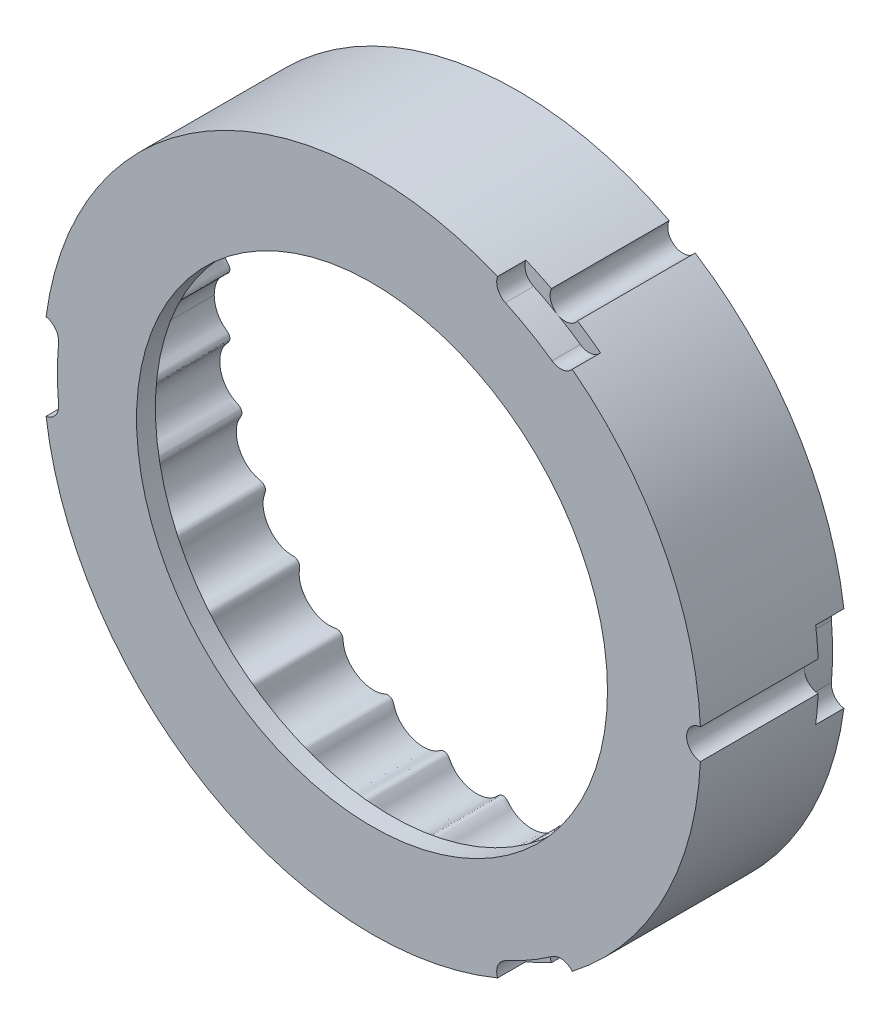
SolidWorks part; units mm, degrees
ref_plane "Plan de face" through (0, 0, 0) normal (0, 0, 1) x (1, 0, 0)
ref_plane "Plan de dessus" through (0, 0, 0) normal (0, 1, 0) x (1, 0, 0)
ref_plane "Plan de droite" through (0, 0, 0) normal (1, 0, 0) x (0, 0, -1)
sketch "Esquisse1" plane through (0, 0, 0) normal (0, 0, 1) x (1, 0, 0)
  line L0 (-1000, 0) -> (49000, 0) construction
  circle A1 centre (0, 0) radius 34.9
  spline S0 degree 4 poles (30.9263, 8.5917) (30.9244, 8.4726) (30.9128, 8.294) (30.8795, 8.0576) (30.8075, 7.7682) (30.7313, 7.5422) (30.6363, 7.3233) (30.5223, 7.1138) (30.4005, 6.9287) (30.2778, 6.7655) (30.1754, 6.608) (30.1146, 6.4469) (30.0971, 6.2542) (30.1421, 6.0755) (30.2337, 5.9301) (30.3636, 5.8076) (30.4814, 5.7308) (30.5967, 5.6632) (30.7272, 5.5824) (30.8546, 5.4968) (31.0375, 5.3568) (31.2617, 5.1464) (31.5493, 4.8022) (31.8437, 4.2901) (32.0606, 3.6436) (32.1377, 2.876) (32.0537, 2.1997) (31.8673, 1.6401) (31.6545, 1.2467) (31.4775, 0.9968) (31.3101, 0.8048) (31.1655, 0.661) (31.0397, 0.5491) (30.944, 0.4561) (30.882, 0.3799) (30.8461, 0.3281) (30.8149, 0.2732) (30.7893, 0.2154) (30.772, 0.1642) (30.7612, 0.1176) (30.7537, 0.0676) (30.7495, 0.0174) (30.7494, -0.0196) (30.7554, -0.0873) (30.767, -0.1466) (30.7842, -0.2016) (30.8067, -0.2559) (30.8409, -0.3211) (30.8874, -0.3891) (30.9471, -0.4581) (31.0185, -0.528) (31.0876, -0.5916) (31.174, -0.6713) (31.275, -0.7696) (31.4187, -0.925) (31.5905, -1.1493) (31.7652, -1.4406) (31.9227, -1.8045) (32.035, -2.1949) (32.0985, -2.6058) (32.1109, -3.0185) (32.074, -3.4266) (31.9897, -3.8245) (31.8596, -4.2068) (31.6858, -4.5663) (31.471, -4.8977) (31.2491, -5.1584) (31.0376, -5.3559) (30.847, -5.5028) (30.6865, -5.6097) (30.5113, -5.713) (30.3279, -5.8265) (30.1731, -5.9986) (30.0932, -6.2291) (30.1102, -6.46) (30.2005, -6.6565) (30.3192, -6.8188) (30.4296, -6.9724) (30.5569, -7.1717) (30.687, -7.4243) (30.8105, -7.7521) (30.9023, -8.158) (30.9393, -8.591) (30.9154, -9.0432) (30.8331, -9.4792) (30.6986, -9.8922) (30.5175, -10.2769) (30.2954, -10.6287) (30.0366, -10.942) (29.747, -11.2129) (29.4704, -11.4101) (29.2233, -11.5472) (29.008, -11.6414) (28.8315, -11.7068) (28.6421, -11.7692) (28.45, -11.8631) (28.2883, -12.027) (28.2103, -12.2249) (28.2035, -12.4054) (28.2368, -12.5701) (28.2938, -12.7158) (28.368, -12.8732) (28.4417, -13.0514) (28.5193, -13.2794) (28.5859, -13.5612) (28.6259, -13.9014) (28.6202, -14.2968) (28.5642, -14.6927) (28.4589, -15.0831) (28.3079, -15.4581) (28.1138, -15.8126) (27.8795, -16.1417) (27.6077, -16.4405) (27.3049, -16.7011) (26.9756, -16.9193) (26.6681, -17.0697) (26.3953, -17.1663) (26.1618, -17.2248) (25.972, -17.2589) (25.7701, -17.2839) (25.5569, -17.3186) (25.349, -17.4213) (25.1897, -17.6061) (25.1202, -17.827) (25.1307, -18.0426) (25.1768, -18.2381) (25.2169, -18.423) (25.254, -18.6564) (25.2723, -18.9399) (25.2546, -19.2896) (25.1768, -19.6983) (25.0382, -20.11) (24.8361, -20.5151) (24.5838, -20.8868) (24.2876, -21.2199) (23.9535, -21.5097) (23.5874, -21.7517) (23.2101, -21.9337) (22.8739, -22.0436) (22.5914, -22.1021) (22.3252, -22.1336) (22.1016, -22.1407) (21.8785, -22.1275) (21.6437, -22.1096) (21.4389, -22.1288) (21.235, -22.2214) (21.0721, -22.3967) (20.993, -22.6129) (20.9856, -22.8294) (20.9927, -23.0328) (20.9891, -23.2256) (20.9691, -23.4656) (20.9175, -23.7504) (20.8184, -24.0782) (20.6555, -24.4384) (20.4463, -24.779) (20.1313, -25.174) (19.6816, -25.5833) (19.1591, -25.8987) (18.5904, -26.1016) (18.1017, -26.1879) (17.7596, -26.203) (17.4709, -26.1826) (17.2335, -26.1428) (17.0458, -26.0984) (16.8505, -26.0411) (16.6399, -25.9918) (16.4106, -26.0101) (16.1979, -26.12) (16.0541, -26.2917) (15.9812, -26.4843) (15.9468, -26.6722) (15.9136, -26.8477) (15.8717, -27.0214) (15.8184, -27.1921) (15.7382, -27.4006) (15.5637, -27.7585) (15.2945, -28.1386) (14.9171, -28.5115) (14.4633, -28.8259) (14.0673, -29.0303) (13.6447, -29.1826) (13.2023, -29.278) (12.7692, -29.3104) (12.354, -29.2847) (12.0109, -29.2154) (11.7407, -29.1278) (11.5237, -29.0341) (11.3545, -28.9495) (11.1772, -28.8554) (10.9723, -28.7881) (10.7409, -28.7959) (10.5202, -28.8997) (10.3654, -29.0728) (10.2765, -29.2698) (10.2021, -29.4592) (10.1221, -29.6346) (10.0078, -29.8465) (9.8467, -30.087) (9.625, -30.3479) (9.2571, -30.6809) (8.748, -31.0055) (8.1785, -31.2248) (7.5795, -31.329) (7.0742, -31.3356) (6.6768, -31.2918) (6.2924, -31.1996) (5.9727, -31.0767) (5.7161, -30.9427) (5.5144, -30.8112) (5.3599, -30.6957) (5.2035, -30.5655) (5.0269, -30.4397) (4.8069, -30.3718) (4.5688, -30.3956) (4.3717, -30.5019) (4.2324, -30.653) (4.1276, -30.8125) (4.0272, -30.9603) (3.9195, -31.1029) (3.8025, -31.238) (3.6457, -31.3971) (3.3428, -31.6554) (2.8502, -31.9535) (2.2369, -32.1596) (1.5733, -32.2322) (1.0155, -32.1965) (0.5716, -32.1077) (0.1613, -31.9647) (-0.2092, -31.7754) (-0.4962, -31.5747) (-0.7089, -31.3863) (-0.8705, -31.2138) (-0.9919, -31.0688) (-1.1186, -30.9128) (-1.2838, -30.7736) (-1.5018, -30.6954) (-1.7453, -30.7105) (-1.9528, -30.8138) (-2.1099, -30.9617) (-2.2535, -31.1059) (-2.3968, -31.2349) (-2.5863, -31.3834) (-2.8299, -31.5395) (-3.1373, -31.6901) (-3.5116, -31.8163) (-3.9031, -31.8956) (-4.3058, -31.9269) (-4.7094, -31.9102) (-5.1084, -31.8461) (-5.4973, -31.7354) (-5.8703, -31.5791) (-6.2174, -31.3804) (-6.5332, -31.1424) (-6.7773, -30.902) (-6.9589, -30.6765) (-7.0914, -30.4753) (-7.1869, -30.3078) (-7.2659, -30.1527) (-7.3469, -30.0188) (-7.4577, -29.8924) (-7.6055, -29.7886) (-7.8103, -29.7311) (-8.0386, -29.7607) (-8.2296, -29.8563) (-8.3948, -29.9679) (-8.5547, -30.0672) (-8.7612, -30.1794) (-9.0211, -30.2905) (-9.3464, -30.3878) (-9.7381, -30.4504) (-10.1442, -30.4625) (-10.5582, -30.4222) (-10.9731, -30.3294) (-11.3818, -30.1823) (-11.7767, -29.98) (-12.1486, -29.7215) (-12.4679, -29.4266) (-12.7322, -29.1051) (-12.9152, -28.8064) (-13.0349, -28.5486) (-13.1142, -28.3258) (-13.1678, -28.1444) (-13.224, -27.9513) (-13.3256, -27.7603) (-13.4992, -27.6071) (-13.731, -27.5313) (-13.9616, -27.5503) (-14.1632, -27.6266) (-14.3522, -27.7017) (-14.535, -27.7628) (-14.7681, -27.8232) (-15.0538, -27.869) (-15.3957, -27.8843) (-15.7892, -27.8507) (-16.2785, -27.7463) (-16.7528, -27.5609) (-17.1946, -27.3015) (-17.5907, -26.9743) (-17.8764, -26.672) (-18.1159, -26.3439) (-18.3067, -25.9962) (-18.4295, -25.6796) (-18.5013, -25.4063) (-18.5394, -25.1743) (-18.559, -24.9871) (-18.5718, -24.7882) (-18.6117, -24.5785) (-18.7262, -24.3789) (-18.8959, -24.2506) (-19.068, -24.1957) (-19.2358, -24.1842) (-19.3915, -24.2014) (-19.5625, -24.2339) (-19.7534, -24.2613) (-19.9935, -24.2801) (-20.283, -24.2751) (-20.6226, -24.2297) (-21.0043, -24.1264) (-21.3741, -23.9741) (-21.7265, -23.7753) (-22.0523, -23.536) (-22.3477, -23.2602) (-22.6084, -22.9516) (-22.8306, -22.6144) (-23.008, -22.2566) (-23.138, -21.8836) (-23.2077, -21.5484) (-23.2339, -21.2603) (-23.2329, -21.0195) (-23.2189, -20.8273) (-23.1931, -20.6255) (-23.1714, -20.4109) (-23.2147, -20.1833) (-23.35, -19.9802) (-23.5441, -19.854) (-23.755, -19.8069) (-23.956, -19.8018) (-24.145, -19.7948) (-24.3804, -19.7731) (-24.6597, -19.7208) (-25.1025, -19.5837) (-25.5719, -19.3339) (-26.0033, -18.993) (-26.3759, -18.5716) (-26.6251, -18.2022) (-26.8231, -17.8067) (-26.9668, -17.3922) (-27.0498, -16.9817) (-27.0732, -16.6288) (-27.06, -16.3406) (-27.0307, -16.1192) (-26.9958, -15.9439) (-26.9493, -15.7714) (-26.894, -15.6014) (-26.8318, -15.421) (-26.7962, -15.2188) (-26.8307, -14.9976) (-26.9558, -14.7937) (-27.1431, -14.6595) (-27.3504, -14.5957) (-27.5492, -14.5518) (-27.7351, -14.5006) (-27.9627, -14.422) (-28.2261, -14.3016) (-28.5192, -14.1246) (-28.8279, -13.8775) (-29.1063, -13.5905) (-29.4109, -13.1873) (-29.6486, -12.7398) (-29.8135, -12.2607) (-29.9002, -11.7631) (-29.9203, -11.3641) (-29.8906, -10.9701) (-29.8207, -10.6349) (-29.7296, -10.3602) (-29.6324, -10.14) (-29.543, -9.9692) (-29.4389, -9.7943) (-29.3367, -9.6039) (-29.2926, -9.3762) (-29.3434, -9.1376) (-29.4773, -8.9486) (-29.655, -8.8263) (-29.838, -8.7434) (-30.0085, -8.6617) (-30.2156, -8.5478) (-30.4507, -8.3882) (-30.716, -8.1598) (-30.9909, -7.8477) (-31.231, -7.4857) (-31.427, -7.0776) (-31.5659, -6.6505) (-31.6473, -6.2122) (-31.6713, -5.7706) (-31.638, -5.3329) (-31.5503, -4.9233) (-31.4308, -4.5902) (-31.3037, -4.3313) (-31.1883, -4.14) (-31.0862, -3.9932) (-30.9747, -3.8536) (-30.8564, -3.7197) (-30.7286, -3.5777) (-30.6197, -3.4032) (-30.57, -3.1848) (-30.6111, -2.949) (-30.7353, -2.7553) (-30.9027, -2.6179) (-31.0677, -2.4988) (-31.2178, -2.3777) (-31.395, -2.2147) (-31.5882, -1.9992) (-31.757, -1.7611) (-31.8999, -1.5043) (-32.0017, -1.2787) (-32.0729, -1.0898) (-32.1322, -0.8972) (-32.1797, -0.7008) (-32.2109, -0.5276) (-32.2302, -0.3771) (-32.2413, -0.2512) (-32.2473, -0.1576) (-32.2503, -0.0299) (-32.2502, 0.0388) (-32.2466, 0.1794) (-32.2393, 0.2769) (-32.2254, 0.4211) (-32.2015, 0.5861) (-32.1629, 0.7796) (-32.104, 0.996) (-32.0305, 1.2085) (-31.9423, 1.415) (-31.8234, 1.6465) (-31.6896, 1.8577) (-31.544, 2.0481) (-31.3892, 2.217) (-31.2566, 2.3437) (-31.1158, 2.461) (-30.9692, 2.571) (-30.8116, 2.6874) (-30.6684, 2.8431) (-30.5791, 3.0569) (-30.5824, 3.2743) (-30.648, 3.4491) (-30.7462, 3.5961) (-30.8554, 3.7195) (-30.9782, 3.8564) (-31.1043, 4.0167) (-31.2467, 4.228) (-31.3916, 4.4977) (-31.5524, 4.9075) (-31.6691, 5.4709) (-31.6776, 6.1306) (-31.5281, 6.8579) (-31.2314, 7.526) (-30.8027, 8.104) (-30.3929, 8.4476) (-30.0923, 8.62) (-29.937, 8.6951) knots 0 0 0 0 0 0.003562 0.005342 0.007123 0.008904 0.010685 0.012466 0.014247 0.015519 0.016792 0.018065 0.019337 0.021229 0.022175 0.02312 0.024649 0.025414 0.026178 0.027707 0.029236 0.032293 0.035351 0.04107 0.046788 0.052507 0.058226 0.06127 0.064314 0.065836 0.067358 0.06888 0.070402 0.070873 0.071343 0.071813 0.072284 0.072754 0.073224 0.073459 0.073695 0.074165 0.074604 0.075042 0.075481 0.07592 0.076358 0.076797 0.077674 0.078377 0.079079 0.079782 0.080484 0.081889 0.083294 0.086104 0.088914 0.092014 0.095114 0.098215 0.101315 0.104325 0.107336 0.110347 0.113357 0.116235 0.119112 0.12055 0.121989 0.123428 0.124866 0.12664 0.128414 0.130187 0.13196 0.133373 0.134786 0.1362 0.137613 0.140439 0.143265 0.146639 0.150014 0.153388 0.156763 0.159865 0.162966 0.166068 0.169169 0.171979 0.174789 0.176194 0.177599 0.179004 0.180409 0.182167 0.183924 0.185706 0.186596 0.187487 0.188927 0.190366 0.191805 0.193245 0.196124 0.199002 0.202017 0.205033 0.208048 0.211063 0.214074 0.217086 0.220098 0.22311 0.225987 0.228865 0.230303 0.231742 0.233181 0.234619 0.236396 0.238172 0.239944 0.241716 0.243129 0.244541 0.245954 0.247367 0.250192 0.253017 0.256391 0.259764 0.263137 0.266511 0.269782 0.273052 0.276323 0.279594 0.282264 0.283598 0.284933 0.287603 0.288938 0.290273 0.291978 0.293684 0.295463 0.297243 0.298682 0.300121 0.30156 0.302999 0.305877 0.308756 0.311769 0.314783 0.317797 0.323824 0.32985 0.332862 0.33574 0.338618 0.340058 0.341497 0.342936 0.344375 0.346152 0.34793 0.349637 0.351344 0.352679 0.354014 0.355349 0.356684 0.358019 0.359354 0.362024 0.368567 0.371839 0.375111 0.378483 0.381856 0.385228 0.388601 0.391426 0.39425 0.395663 0.397075 0.398488 0.3999 0.401672 0.403443 0.40522 0.406997 0.408436 0.409875 0.411314 0.412753 0.415631 0.418509 0.421521 0.427546 0.433573 0.436587 0.439601 0.442616 0.445494 0.448372 0.449812 0.451251 0.45269 0.454129 0.455909 0.457689 0.459394 0.461099 0.462434 0.463768 0.465103 0.466438 0.467773 0.469108 0.471777 0.478318 0.484859 0.488232 0.491606 0.49498 0.498354 0.501179 0.504005 0.505418 0.50683 0.508243 0.509656 0.511429 0.513201 0.514977 0.516752 0.518191 0.519629 0.521068 0.522507 0.525384 0.528261 0.531273 0.534284 0.537295 0.540307 0.543322 0.546338 0.549353 0.552369 0.555248 0.558127 0.559566 0.561006 0.562445 0.563885 0.564776 0.565667 0.567449 0.569206 0.570963 0.572368 0.573772 0.575177 0.576582 0.579392 0.582202 0.585303 0.588404 0.591505 0.594606 0.597981 0.601356 0.604731 0.608106 0.610932 0.613759 0.615172 0.616585 0.617999 0.619412 0.621185 0.622958 0.624731 0.626505 0.627943 0.629382 0.63082 0.632259 0.635136 0.638013 0.641024 0.644034 0.650055 0.653155 0.656256 0.659357 0.662457 0.665267 0.668077 0.669482 0.670887 0.672292 0.673697 0.675453 0.677208 0.678992 0.679883 0.680775 0.682214 0.683654 0.685093 0.686533 0.689412 0.69229 0.695306 0.698322 0.701338 0.704354 0.707365 0.710376 0.713387 0.716398 0.719275 0.722153 0.723591 0.72503 0.726469 0.727907 0.729682 0.731457 0.73323 0.735002 0.736415 0.737828 0.739241 0.740654 0.74348 0.746306 0.753054 0.756428 0.759802 0.763072 0.766342 0.769612 0.772882 0.775551 0.776886 0.778221 0.779556 0.780891 0.782226 0.78356 0.785264 0.786968 0.788749 0.790529 0.791969 0.793408 0.794847 0.796287 0.799165 0.802044 0.805058 0.808073 0.811088 0.817114 0.820127 0.823139 0.826151 0.829028 0.831906 0.833345 0.834784 0.836223 0.837661 0.839438 0.841215 0.842986 0.844758 0.846171 0.847583 0.848996 0.850409 0.853234 0.856059 0.859432 0.862805 0.866178 0.86955 0.872822 0.876093 0.879364 0.882635 0.885305 0.88664 0.887975 0.88931 0.890645 0.89198 0.893315 0.895021 0.896727 0.898506 0.900284 0.901724 0.903163 0.904602 0.906041 0.908919 0.911797 0.913304 0.91481 0.916317 0.917824 0.91933 0.920837 0.92159 0.922344 0.923097 0.92385 0.924689 0.925528 0.926367 0.927206 0.928883 0.930561 0.932238 0.933916 0.935594 0.937271 0.94001 0.941379 0.942748 0.944117 0.945486 0.946856 0.948225 0.949976 0.951727 0.9536 0.954537 0.955474 0.956996 0.958518 0.96004 0.961563 0.964607 0.967651 0.973159 0.978666 0.984174 0.989682 0.994841 1 1 1 1 1 construction
  spline S1 degree 4 poles (30.75, 0) (30.75, -0.0125) (30.751, -0.0374) (30.7554, -0.0873) (30.767, -0.1466) (30.7842, -0.2016) (30.8067, -0.2559) (30.8409, -0.3211) (30.8874, -0.3891) (30.9471, -0.4581) (31.0185, -0.528) (31.0876, -0.5916) (31.174, -0.6713) (31.275, -0.7696) (31.4187, -0.925) (31.5905, -1.1493) (31.7652, -1.4406) (31.9227, -1.8045) (32.035, -2.1949) (32.0985, -2.6058) (32.1109, -3.0185) (32.074, -3.4266) (31.9897, -3.8245) (31.8596, -4.2068) (31.6858, -4.5663) (31.471, -4.8977) (31.2491, -5.1584) (31.0376, -5.3559) (30.847, -5.5028) (30.6865, -5.6097) (30.5113, -5.713) (30.3279, -5.8265) (30.1731, -5.9986) (30.0932, -6.2291) (30.1102, -6.46) (30.2005, -6.6565) (30.3192, -6.8188) (30.4296, -6.9724) (30.5569, -7.1717) (30.687, -7.4243) (30.8105, -7.7521) (30.9023, -8.158) (30.9393, -8.591) (30.9154, -9.0432) (30.8331, -9.4792) (30.6986, -9.8922) (30.5175, -10.2769) (30.2954, -10.6287) (30.0366, -10.942) (29.747, -11.2129) (29.4704, -11.4101) (29.2233, -11.5472) (29.008, -11.6414) (28.8315, -11.7068) (28.6421, -11.7692) (28.45, -11.8631) (28.2883, -12.027) (28.2103, -12.2249) (28.2035, -12.4054) (28.2368, -12.5701) (28.2938, -12.7158) (28.368, -12.8732) (28.4417, -13.0514) (28.5193, -13.2794) (28.5859, -13.5612) (28.6259, -13.9014) (28.6202, -14.2968) (28.5642, -14.6927) (28.4589, -15.0831) (28.3079, -15.4581) (28.1138, -15.8126) (27.8795, -16.1417) (27.6077, -16.4405) (27.3049, -16.7011) (26.9756, -16.9193) (26.6681, -17.0697) (26.3953, -17.1663) (26.1618, -17.2248) (25.972, -17.2589) (25.7701, -17.2839) (25.5569, -17.3186) (25.349, -17.4213) (25.1897, -17.6061) (25.1202, -17.827) (25.1307, -18.0426) (25.1768, -18.2381) (25.2169, -18.423) (25.254, -18.6564) (25.2723, -18.9399) (25.2546, -19.2896) (25.1768, -19.6983) (25.0382, -20.11) (24.8361, -20.5151) (24.5838, -20.8868) (24.2876, -21.2199) (23.9535, -21.5097) (23.5874, -21.7517) (23.2101, -21.9337) (22.8739, -22.0436) (22.5914, -22.1021) (22.3252, -22.1336) (22.1016, -22.1407) (21.8785, -22.1275) (21.6437, -22.1096) (21.4389, -22.1288) (21.235, -22.2214) (21.0721, -22.3967) (20.993, -22.6129) (20.9856, -22.8294) (20.9927, -23.0328) (20.9891, -23.2256) (20.9691, -23.4656) (20.9175, -23.7504) (20.8184, -24.0782) (20.6555, -24.4384) (20.4463, -24.779) (20.1313, -25.174) (19.6816, -25.5833) (19.1591, -25.8987) (18.5904, -26.1016) (18.1017, -26.1879) (17.7596, -26.203) (17.4709, -26.1826) (17.2335, -26.1428) (17.0458, -26.0984) (16.8505, -26.0411) (16.6399, -25.9918) (16.4106, -26.0101) (16.1979, -26.12) (16.0541, -26.2917) (15.9812, -26.4843) (15.9468, -26.6722) (15.9136, -26.8477) (15.8717, -27.0214) (15.8184, -27.1921) (15.7382, -27.4006) (15.5637, -27.7585) (15.2945, -28.1386) (14.9171, -28.5115) (14.4633, -28.8259) (14.0673, -29.0303) (13.6447, -29.1826) (13.2023, -29.278) (12.7692, -29.3104) (12.354, -29.2847) (12.0109, -29.2154) (11.7407, -29.1278) (11.5237, -29.0341) (11.3545, -28.9495) (11.1772, -28.8554) (10.9723, -28.7881) (10.7409, -28.7959) (10.5202, -28.8997) (10.3654, -29.0728) (10.2765, -29.2698) (10.2021, -29.4592) (10.1221, -29.6346) (10.0078, -29.8465) (9.8467, -30.087) (9.625, -30.3479) (9.2571, -30.6809) (8.748, -31.0055) (8.1785, -31.2248) (7.5795, -31.329) (7.0742, -31.3356) (6.6768, -31.2918) (6.2924, -31.1996) (5.9727, -31.0767) (5.7161, -30.9427) (5.5144, -30.8112) (5.3599, -30.6957) (5.2035, -30.5655) (5.0269, -30.4397) (4.8069, -30.3718) (4.5688, -30.3956) (4.3717, -30.5019) (4.2324, -30.653) (4.1276, -30.8125) (4.0272, -30.9603) (3.9195, -31.1029) (3.8025, -31.238) (3.6457, -31.3971) (3.3428, -31.6554) (2.8502, -31.9535) (2.2369, -32.1596) (1.5733, -32.2322) (1.0155, -32.1965) (0.5716, -32.1077) (0.1613, -31.9647) (-0.2092, -31.7754) (-0.4962, -31.5747) (-0.7089, -31.3863) (-0.8705, -31.2138) (-0.9919, -31.0688) (-1.1186, -30.9128) (-1.2838, -30.7736) (-1.5018, -30.6954) (-1.7453, -30.7105) (-1.9528, -30.8138) (-2.1099, -30.9617) (-2.2535, -31.1059) (-2.3968, -31.2349) (-2.5863, -31.3834) (-2.8299, -31.5395) (-3.1373, -31.6901) (-3.5116, -31.8163) (-3.9031, -31.8956) (-4.3058, -31.9269) (-4.7094, -31.9102) (-5.1084, -31.8461) (-5.4973, -31.7354) (-5.8703, -31.5791) (-6.2174, -31.3804) (-6.5332, -31.1424) (-6.7773, -30.902) (-6.9589, -30.6765) (-7.0914, -30.4753) (-7.1869, -30.3078) (-7.2659, -30.1527) (-7.3469, -30.0188) (-7.4577, -29.8924) (-7.6055, -29.7886) (-7.8103, -29.7311) (-8.0386, -29.7607) (-8.2296, -29.8563) (-8.3948, -29.9679) (-8.5547, -30.0672) (-8.7612, -30.1794) (-9.0211, -30.2905) (-9.3464, -30.3878) (-9.7381, -30.4504) (-10.1442, -30.4625) (-10.5582, -30.4222) (-10.9731, -30.3294) (-11.3818, -30.1823) (-11.7767, -29.98) (-12.1486, -29.7215) (-12.4679, -29.4266) (-12.7322, -29.1051) (-12.9152, -28.8064) (-13.0349, -28.5486) (-13.1142, -28.3258) (-13.1678, -28.1444) (-13.224, -27.9513) (-13.3256, -27.7603) (-13.4992, -27.6071) (-13.731, -27.5313) (-13.9616, -27.5503) (-14.1632, -27.6266) (-14.3522, -27.7017) (-14.535, -27.7628) (-14.7681, -27.8232) (-15.0538, -27.869) (-15.3957, -27.8843) (-15.7892, -27.8507) (-16.2785, -27.7463) (-16.7528, -27.5609) (-17.1946, -27.3015) (-17.5907, -26.9743) (-17.8764, -26.672) (-18.1159, -26.3439) (-18.3067, -25.9962) (-18.4295, -25.6796) (-18.5013, -25.4063) (-18.5394, -25.1743) (-18.559, -24.9871) (-18.5718, -24.7882) (-18.6117, -24.5785) (-18.7262, -24.3789) (-18.8959, -24.2506) (-19.068, -24.1957) (-19.2358, -24.1842) (-19.3915, -24.2014) (-19.5625, -24.2339) (-19.7534, -24.2613) (-19.9935, -24.2801) (-20.283, -24.2751) (-20.6226, -24.2297) (-21.0043, -24.1264) (-21.3741, -23.9741) (-21.7265, -23.7753) (-22.0523, -23.536) (-22.3477, -23.2602) (-22.6084, -22.9516) (-22.8306, -22.6144) (-23.008, -22.2566) (-23.138, -21.8836) (-23.2077, -21.5484) (-23.2339, -21.2603) (-23.2329, -21.0195) (-23.2189, -20.8273) (-23.1931, -20.6255) (-23.1714, -20.4109) (-23.2147, -20.1833) (-23.35, -19.9802) (-23.5441, -19.854) (-23.755, -19.8069) (-23.956, -19.8018) (-24.145, -19.7948) (-24.3804, -19.7731) (-24.6597, -19.7208) (-25.1025, -19.5837) (-25.5719, -19.3339) (-26.0033, -18.993) (-26.3759, -18.5716) (-26.6251, -18.2022) (-26.8231, -17.8067) (-26.9668, -17.3922) (-27.0498, -16.9817) (-27.0732, -16.6288) (-27.06, -16.3406) (-27.0307, -16.1192) (-26.9958, -15.9439) (-26.9493, -15.7714) (-26.894, -15.6014) (-26.8318, -15.421) (-26.7962, -15.2188) (-26.8307, -14.9976) (-26.9558, -14.7937) (-27.1431, -14.6595) (-27.3504, -14.5957) (-27.5492, -14.5518) (-27.7351, -14.5006) (-27.9627, -14.422) (-28.2261, -14.3016) (-28.5192, -14.1246) (-28.8279, -13.8775) (-29.1063, -13.5905) (-29.4109, -13.1873) (-29.6486, -12.7398) (-29.8135, -12.2607) (-29.9002, -11.7631) (-29.9203, -11.3641) (-29.8906, -10.9701) (-29.8207, -10.6349) (-29.7296, -10.3602) (-29.6324, -10.14) (-29.543, -9.9692) (-29.4389, -9.7943) (-29.3367, -9.6039) (-29.2926, -9.3762) (-29.3434, -9.1376) (-29.4773, -8.9486) (-29.655, -8.8263) (-29.838, -8.7434) (-30.0085, -8.6617) (-30.2156, -8.5478) (-30.4507, -8.3882) (-30.716, -8.1598) (-30.9909, -7.8477) (-31.231, -7.4857) (-31.427, -7.0776) (-31.5659, -6.6505) (-31.6473, -6.2122) (-31.6713, -5.7706) (-31.638, -5.3329) (-31.5503, -4.9233) (-31.4308, -4.5902) (-31.3037, -4.3313) (-31.1883, -4.14) (-31.0862, -3.9932) (-30.9747, -3.8536) (-30.8564, -3.7197) (-30.7286, -3.5777) (-30.6197, -3.4032) (-30.57, -3.1848) (-30.6111, -2.949) (-30.7353, -2.7553) (-30.9027, -2.6179) (-31.0677, -2.4988) (-31.2178, -2.3777) (-31.395, -2.2147) (-31.5882, -1.9992) (-31.757, -1.7611) (-31.8999, -1.5043) (-32.0017, -1.2787) (-32.0729, -1.0898) (-32.1322, -0.8972) (-32.1797, -0.7008) (-32.2109, -0.5276) (-32.2302, -0.3771) (-32.2413, -0.2512) (-32.2473, -0.1576) (-32.2495, -0.0645) (-32.25, -0.0214) (-32.25, 0) knots 0.074165 0.074165 0.074165 0.074165 0.074165 0.074604 0.075042 0.075481 0.07592 0.076358 0.076797 0.077674 0.078377 0.079079 0.079782 0.080484 0.081889 0.083294 0.086104 0.088914 0.092014 0.095114 0.098215 0.101315 0.104325 0.107336 0.110347 0.113357 0.116235 0.119112 0.12055 0.121989 0.123428 0.124866 0.12664 0.128414 0.130187 0.13196 0.133373 0.134786 0.1362 0.137613 0.140439 0.143265 0.146639 0.150014 0.153388 0.156763 0.159865 0.162966 0.166068 0.169169 0.171979 0.174789 0.176194 0.177599 0.179004 0.180409 0.182167 0.183924 0.185706 0.186596 0.187487 0.188927 0.190366 0.191805 0.193245 0.196124 0.199002 0.202017 0.205033 0.208048 0.211063 0.214074 0.217086 0.220098 0.22311 0.225987 0.228865 0.230303 0.231742 0.233181 0.234619 0.236396 0.238172 0.239944 0.241716 0.243129 0.244541 0.245954 0.247367 0.250192 0.253017 0.256391 0.259764 0.263137 0.266511 0.269782 0.273052 0.276323 0.279594 0.282264 0.283598 0.284933 0.287603 0.288938 0.290273 0.291978 0.293684 0.295463 0.297243 0.298682 0.300121 0.30156 0.302999 0.305877 0.308756 0.311769 0.314783 0.317797 0.323824 0.32985 0.332862 0.33574 0.338618 0.340058 0.341497 0.342936 0.344375 0.346152 0.34793 0.349637 0.351344 0.352679 0.354014 0.355349 0.356684 0.358019 0.359354 0.362024 0.368567 0.371839 0.375111 0.378483 0.381856 0.385228 0.388601 0.391426 0.39425 0.395663 0.397075 0.398488 0.3999 0.401672 0.403443 0.40522 0.406997 0.408436 0.409875 0.411314 0.412753 0.415631 0.418509 0.421521 0.427546 0.433573 0.436587 0.439601 0.442616 0.445494 0.448372 0.449812 0.451251 0.45269 0.454129 0.455909 0.457689 0.459394 0.461099 0.462434 0.463768 0.465103 0.466438 0.467773 0.469108 0.471777 0.478318 0.484859 0.488232 0.491606 0.49498 0.498354 0.501179 0.504005 0.505418 0.50683 0.508243 0.509656 0.511429 0.513201 0.514977 0.516752 0.518191 0.519629 0.521068 0.522507 0.525384 0.528261 0.531273 0.534284 0.537295 0.540307 0.543322 0.546338 0.549353 0.552369 0.555248 0.558127 0.559566 0.561006 0.562445 0.563885 0.564776 0.565667 0.567449 0.569206 0.570963 0.572368 0.573772 0.575177 0.576582 0.579392 0.582202 0.585303 0.588404 0.591505 0.594606 0.597981 0.601356 0.604731 0.608106 0.610932 0.613759 0.615172 0.616585 0.617999 0.619412 0.621185 0.622958 0.624731 0.626505 0.627943 0.629382 0.63082 0.632259 0.635136 0.638013 0.641024 0.644034 0.650055 0.653155 0.656256 0.659357 0.662457 0.665267 0.668077 0.669482 0.670887 0.672292 0.673697 0.675453 0.677208 0.678992 0.679883 0.680775 0.682214 0.683654 0.685093 0.686533 0.689412 0.69229 0.695306 0.698322 0.701338 0.704354 0.707365 0.710376 0.713387 0.716398 0.719275 0.722153 0.723591 0.72503 0.726469 0.727907 0.729682 0.731457 0.73323 0.735002 0.736415 0.737828 0.739241 0.740654 0.74348 0.746306 0.753054 0.756428 0.759802 0.763072 0.766342 0.769612 0.772882 0.775551 0.776886 0.778221 0.779556 0.780891 0.782226 0.78356 0.785264 0.786968 0.788749 0.790529 0.791969 0.793408 0.794847 0.796287 0.799165 0.802044 0.805058 0.808073 0.811088 0.817114 0.820127 0.823139 0.826151 0.829028 0.831906 0.833345 0.834784 0.836223 0.837661 0.839438 0.841215 0.842986 0.844758 0.846171 0.847583 0.848996 0.850409 0.853234 0.856059 0.859432 0.862805 0.866178 0.86955 0.872822 0.876093 0.879364 0.882635 0.885305 0.88664 0.887975 0.88931 0.890645 0.89198 0.893315 0.895021 0.896727 0.898506 0.900284 0.901724 0.903163 0.904602 0.906041 0.908919 0.911797 0.913304 0.91481 0.916317 0.917824 0.91933 0.920837 0.92159 0.922344 0.923097 0.92385 0.92385 0.92385 0.92385 0.92385
  spline S2 degree 4 poles (30.75, 0) (30.75, 0.0125) (30.751, 0.0374) (30.7554, 0.0873) (30.767, 0.1466) (30.7842, 0.2016) (30.8067, 0.2559) (30.8409, 0.3211) (30.8874, 0.3891) (30.9471, 0.4581) (31.0185, 0.528) (31.0876, 0.5916) (31.174, 0.6713) (31.275, 0.7696) (31.4187, 0.925) (31.5905, 1.1493) (31.7652, 1.4406) (31.9227, 1.8045) (32.035, 2.1949) (32.0985, 2.6058) (32.1109, 3.0185) (32.074, 3.4266) (31.9897, 3.8245) (31.8596, 4.2068) (31.6858, 4.5663) (31.471, 4.8977) (31.2491, 5.1584) (31.0376, 5.3559) (30.847, 5.5028) (30.6865, 5.6097) (30.5113, 5.713) (30.3279, 5.8265) (30.1731, 5.9986) (30.0932, 6.2291) (30.1102, 6.46) (30.2005, 6.6565) (30.3192, 6.8188) (30.4296, 6.9724) (30.5569, 7.1717) (30.687, 7.4243) (30.8105, 7.7521) (30.9023, 8.158) (30.9393, 8.591) (30.9154, 9.0432) (30.8331, 9.4792) (30.6986, 9.8922) (30.5175, 10.2769) (30.2954, 10.6287) (30.0366, 10.942) (29.747, 11.2129) (29.4704, 11.4101) (29.2233, 11.5472) (29.008, 11.6414) (28.8315, 11.7068) (28.6421, 11.7692) (28.45, 11.8631) (28.2883, 12.027) (28.2103, 12.2249) (28.2035, 12.4054) (28.2368, 12.5701) (28.2938, 12.7158) (28.368, 12.8732) (28.4417, 13.0514) (28.5193, 13.2794) (28.5859, 13.5612) (28.6259, 13.9014) (28.6202, 14.2968) (28.5642, 14.6927) (28.4589, 15.0831) (28.3079, 15.4581) (28.1138, 15.8126) (27.8795, 16.1417) (27.6077, 16.4405) (27.3049, 16.7011) (26.9756, 16.9193) (26.6681, 17.0697) (26.3953, 17.1663) (26.1618, 17.2248) (25.972, 17.2589) (25.7701, 17.2839) (25.5569, 17.3186) (25.349, 17.4213) (25.1897, 17.6061) (25.1202, 17.827) (25.1307, 18.0426) (25.1768, 18.2381) (25.2169, 18.423) (25.254, 18.6564) (25.2723, 18.9399) (25.2546, 19.2896) (25.1768, 19.6983) (25.0382, 20.11) (24.8361, 20.5151) (24.5838, 20.8868) (24.2876, 21.2199) (23.9535, 21.5097) (23.5874, 21.7517) (23.2101, 21.9337) (22.8739, 22.0436) (22.5914, 22.1021) (22.3252, 22.1336) (22.1016, 22.1407) (21.8785, 22.1275) (21.6437, 22.1096) (21.4389, 22.1288) (21.235, 22.2214) (21.0721, 22.3967) (20.993, 22.6129) (20.9856, 22.8294) (20.9927, 23.0328) (20.9891, 23.2256) (20.9691, 23.4656) (20.9175, 23.7504) (20.8184, 24.0782) (20.6555, 24.4384) (20.4463, 24.779) (20.1313, 25.174) (19.6816, 25.5833) (19.1591, 25.8987) (18.5904, 26.1016) (18.1017, 26.1879) (17.7596, 26.203) (17.4709, 26.1826) (17.2335, 26.1428) (17.0458, 26.0984) (16.8505, 26.0411) (16.6399, 25.9918) (16.4106, 26.0101) (16.1979, 26.12) (16.0541, 26.2917) (15.9812, 26.4843) (15.9468, 26.6722) (15.9136, 26.8477) (15.8717, 27.0214) (15.8184, 27.1921) (15.7382, 27.4006) (15.5637, 27.7585) (15.2945, 28.1386) (14.9171, 28.5115) (14.4633, 28.8259) (14.0673, 29.0303) (13.6447, 29.1826) (13.2023, 29.278) (12.7692, 29.3104) (12.354, 29.2847) (12.0109, 29.2154) (11.7407, 29.1278) (11.5237, 29.0341) (11.3545, 28.9495) (11.1772, 28.8554) (10.9723, 28.7881) (10.7409, 28.7959) (10.5202, 28.8997) (10.3654, 29.0728) (10.2765, 29.2698) (10.2021, 29.4592) (10.1221, 29.6346) (10.0078, 29.8465) (9.8467, 30.087) (9.625, 30.3479) (9.2571, 30.6809) (8.748, 31.0055) (8.1785, 31.2248) (7.5795, 31.329) (7.0742, 31.3356) (6.6768, 31.2918) (6.2924, 31.1996) (5.9727, 31.0767) (5.7161, 30.9427) (5.5144, 30.8112) (5.3599, 30.6957) (5.2035, 30.5655) (5.0269, 30.4397) (4.8069, 30.3718) (4.5688, 30.3956) (4.3717, 30.5019) (4.2324, 30.653) (4.1276, 30.8125) (4.0272, 30.9603) (3.9195, 31.1029) (3.8025, 31.238) (3.6457, 31.3971) (3.3428, 31.6554) (2.8502, 31.9535) (2.2369, 32.1596) (1.5733, 32.2322) (1.0155, 32.1965) (0.5716, 32.1077) (0.1613, 31.9647) (-0.2092, 31.7754) (-0.4962, 31.5747) (-0.7089, 31.3863) (-0.8705, 31.2138) (-0.9919, 31.0688) (-1.1186, 30.9128) (-1.2838, 30.7736) (-1.5018, 30.6954) (-1.7453, 30.7105) (-1.9528, 30.8138) (-2.1099, 30.9617) (-2.2535, 31.1059) (-2.3968, 31.2349) (-2.5863, 31.3834) (-2.8299, 31.5395) (-3.1373, 31.6901) (-3.5116, 31.8163) (-3.9031, 31.8956) (-4.3058, 31.9269) (-4.7094, 31.9102) (-5.1084, 31.8461) (-5.4973, 31.7354) (-5.8703, 31.5791) (-6.2174, 31.3804) (-6.5332, 31.1424) (-6.7773, 30.902) (-6.9589, 30.6765) (-7.0914, 30.4753) (-7.1869, 30.3078) (-7.2659, 30.1527) (-7.3469, 30.0188) (-7.4577, 29.8924) (-7.6055, 29.7886) (-7.8103, 29.7311) (-8.0386, 29.7607) (-8.2296, 29.8563) (-8.3948, 29.9679) (-8.5547, 30.0672) (-8.7612, 30.1794) (-9.0211, 30.2905) (-9.3464, 30.3878) (-9.7381, 30.4504) (-10.1442, 30.4625) (-10.5582, 30.4222) (-10.9731, 30.3294) (-11.3818, 30.1823) (-11.7767, 29.98) (-12.1486, 29.7215) (-12.4679, 29.4266) (-12.7322, 29.1051) (-12.9152, 28.8064) (-13.0349, 28.5486) (-13.1142, 28.3258) (-13.1678, 28.1444) (-13.224, 27.9513) (-13.3256, 27.7603) (-13.4992, 27.6071) (-13.731, 27.5313) (-13.9616, 27.5503) (-14.1632, 27.6266) (-14.3522, 27.7017) (-14.535, 27.7628) (-14.7681, 27.8232) (-15.0538, 27.869) (-15.3957, 27.8843) (-15.7892, 27.8507) (-16.2785, 27.7463) (-16.7528, 27.5609) (-17.1946, 27.3015) (-17.5907, 26.9743) (-17.8764, 26.672) (-18.1159, 26.3439) (-18.3067, 25.9962) (-18.4295, 25.6796) (-18.5013, 25.4063) (-18.5394, 25.1743) (-18.559, 24.9871) (-18.5718, 24.7882) (-18.6117, 24.5785) (-18.7262, 24.3789) (-18.8959, 24.2506) (-19.068, 24.1957) (-19.2358, 24.1842) (-19.3915, 24.2014) (-19.5625, 24.2339) (-19.7534, 24.2613) (-19.9935, 24.2801) (-20.283, 24.2751) (-20.6226, 24.2297) (-21.0043, 24.1264) (-21.3741, 23.9741) (-21.7265, 23.7753) (-22.0523, 23.536) (-22.3477, 23.2602) (-22.6084, 22.9516) (-22.8306, 22.6144) (-23.008, 22.2566) (-23.138, 21.8836) (-23.2077, 21.5484) (-23.2339, 21.2603) (-23.2329, 21.0195) (-23.2189, 20.8273) (-23.1931, 20.6255) (-23.1714, 20.4109) (-23.2147, 20.1833) (-23.35, 19.9802) (-23.5441, 19.854) (-23.755, 19.8069) (-23.956, 19.8018) (-24.145, 19.7948) (-24.3804, 19.7731) (-24.6597, 19.7208) (-25.1025, 19.5837) (-25.5719, 19.3339) (-26.0033, 18.993) (-26.3759, 18.5716) (-26.6251, 18.2022) (-26.8231, 17.8067) (-26.9668, 17.3922) (-27.0498, 16.9817) (-27.0732, 16.6288) (-27.06, 16.3406) (-27.0307, 16.1192) (-26.9958, 15.9439) (-26.9493, 15.7714) (-26.894, 15.6014) (-26.8318, 15.421) (-26.7962, 15.2188) (-26.8307, 14.9976) (-26.9558, 14.7937) (-27.1431, 14.6595) (-27.3504, 14.5957) (-27.5492, 14.5518) (-27.7351, 14.5006) (-27.9627, 14.422) (-28.2261, 14.3016) (-28.5192, 14.1246) (-28.8279, 13.8775) (-29.1063, 13.5905) (-29.4109, 13.1873) (-29.6486, 12.7398) (-29.8135, 12.2607) (-29.9002, 11.7631) (-29.9203, 11.3641) (-29.8906, 10.9701) (-29.8207, 10.6349) (-29.7296, 10.3602) (-29.6324, 10.14) (-29.543, 9.9692) (-29.4389, 9.7943) (-29.3367, 9.6039) (-29.2926, 9.3762) (-29.3434, 9.1376) (-29.4773, 8.9486) (-29.655, 8.8263) (-29.838, 8.7434) (-30.0085, 8.6617) (-30.2156, 8.5478) (-30.4507, 8.3882) (-30.716, 8.1598) (-30.9909, 7.8477) (-31.231, 7.4857) (-31.427, 7.0776) (-31.5659, 6.6505) (-31.6473, 6.2122) (-31.6713, 5.7706) (-31.638, 5.3329) (-31.5503, 4.9233) (-31.4308, 4.5902) (-31.3037, 4.3313) (-31.1883, 4.14) (-31.0862, 3.9932) (-30.9747, 3.8536) (-30.8564, 3.7197) (-30.7286, 3.5777) (-30.6197, 3.4032) (-30.57, 3.1848) (-30.6111, 2.949) (-30.7353, 2.7553) (-30.9027, 2.6179) (-31.0677, 2.4988) (-31.2178, 2.3777) (-31.395, 2.2147) (-31.5882, 1.9992) (-31.757, 1.7611) (-31.8999, 1.5043) (-32.0017, 1.2787) (-32.0729, 1.0898) (-32.1322, 0.8972) (-32.1797, 0.7008) (-32.2109, 0.5276) (-32.2302, 0.3771) (-32.2413, 0.2512) (-32.2473, 0.1576) (-32.2495, 0.0645) (-32.25, 0.0214) (-32.25, 0) knots 0.074165 0.074165 0.074165 0.074165 0.074165 0.074604 0.075042 0.075481 0.07592 0.076358 0.076797 0.077674 0.078377 0.079079 0.079782 0.080484 0.081889 0.083294 0.086104 0.088914 0.092014 0.095114 0.098215 0.101315 0.104325 0.107336 0.110347 0.113357 0.116235 0.119112 0.12055 0.121989 0.123428 0.124866 0.12664 0.128414 0.130187 0.13196 0.133373 0.134786 0.1362 0.137613 0.140439 0.143265 0.146639 0.150014 0.153388 0.156763 0.159865 0.162966 0.166068 0.169169 0.171979 0.174789 0.176194 0.177599 0.179004 0.180409 0.182167 0.183924 0.185706 0.186596 0.187487 0.188927 0.190366 0.191805 0.193245 0.196124 0.199002 0.202017 0.205033 0.208048 0.211063 0.214074 0.217086 0.220098 0.22311 0.225987 0.228865 0.230303 0.231742 0.233181 0.234619 0.236396 0.238172 0.239944 0.241716 0.243129 0.244541 0.245954 0.247367 0.250192 0.253017 0.256391 0.259764 0.263137 0.266511 0.269782 0.273052 0.276323 0.279594 0.282264 0.283598 0.284933 0.287603 0.288938 0.290273 0.291978 0.293684 0.295463 0.297243 0.298682 0.300121 0.30156 0.302999 0.305877 0.308756 0.311769 0.314783 0.317797 0.323824 0.32985 0.332862 0.33574 0.338618 0.340058 0.341497 0.342936 0.344375 0.346152 0.34793 0.349637 0.351344 0.352679 0.354014 0.355349 0.356684 0.358019 0.359354 0.362024 0.368567 0.371839 0.375111 0.378483 0.381856 0.385228 0.388601 0.391426 0.39425 0.395663 0.397075 0.398488 0.3999 0.401672 0.403443 0.40522 0.406997 0.408436 0.409875 0.411314 0.412753 0.415631 0.418509 0.421521 0.427546 0.433573 0.436587 0.439601 0.442616 0.445494 0.448372 0.449812 0.451251 0.45269 0.454129 0.455909 0.457689 0.459394 0.461099 0.462434 0.463768 0.465103 0.466438 0.467773 0.469108 0.471777 0.478318 0.484859 0.488232 0.491606 0.49498 0.498354 0.501179 0.504005 0.505418 0.50683 0.508243 0.509656 0.511429 0.513201 0.514977 0.516752 0.518191 0.519629 0.521068 0.522507 0.525384 0.528261 0.531273 0.534284 0.537295 0.540307 0.543322 0.546338 0.549353 0.552369 0.555248 0.558127 0.559566 0.561006 0.562445 0.563885 0.564776 0.565667 0.567449 0.569206 0.570963 0.572368 0.573772 0.575177 0.576582 0.579392 0.582202 0.585303 0.588404 0.591505 0.594606 0.597981 0.601356 0.604731 0.608106 0.610932 0.613759 0.615172 0.616585 0.617999 0.619412 0.621185 0.622958 0.624731 0.626505 0.627943 0.629382 0.63082 0.632259 0.635136 0.638013 0.641024 0.644034 0.650055 0.653155 0.656256 0.659357 0.662457 0.665267 0.668077 0.669482 0.670887 0.672292 0.673697 0.675453 0.677208 0.678992 0.679883 0.680775 0.682214 0.683654 0.685093 0.686533 0.689412 0.69229 0.695306 0.698322 0.701338 0.704354 0.707365 0.710376 0.713387 0.716398 0.719275 0.722153 0.723591 0.72503 0.726469 0.727907 0.729682 0.731457 0.73323 0.735002 0.736415 0.737828 0.739241 0.740654 0.74348 0.746306 0.753054 0.756428 0.759802 0.763072 0.766342 0.769612 0.772882 0.775551 0.776886 0.778221 0.779556 0.780891 0.782226 0.78356 0.785264 0.786968 0.788749 0.790529 0.791969 0.793408 0.794847 0.796287 0.799165 0.802044 0.805058 0.808073 0.811088 0.817114 0.820127 0.823139 0.826151 0.829028 0.831906 0.833345 0.834784 0.836223 0.837661 0.839438 0.841215 0.842986 0.844758 0.846171 0.847583 0.848996 0.850409 0.853234 0.856059 0.859432 0.862805 0.866178 0.86955 0.872822 0.876093 0.879364 0.882635 0.885305 0.88664 0.887975 0.88931 0.890645 0.89198 0.893315 0.895021 0.896727 0.898506 0.900284 0.901724 0.903163 0.904602 0.906041 0.908919 0.911797 0.913304 0.91481 0.916317 0.917824 0.91933 0.920837 0.92159 0.922344 0.923097 0.92385 0.92385 0.92385 0.92385 0.92385
  dimension "D1" = 69.8
extrude "Boss.-Extru.1" add sketch "Esquisse1" along normal blind 13.5
sketch "Esquisse3" plane through (0, 0, 13.5) normal (0, 0, 1) x (1, 0, 0)
  circle A0 centre (0, 0) radius 25
  circle A1 centre (0, 0) radius 34.9
  circle A2 centre (0, 0) radius 34.9 construction
  dimension "D1" = 50
extrude "Boss.-Extru.2" add sketch "Esquisse3" along normal blind 2
sketch "Esquisse4" plane through (0, 0, 15.5) normal (0, 0, 1) x (1, 0, 0)
  circle A13 centre (0, 0) radius 35 construction
  circle A14 centre (-35, 0) radius 1.6
  circle A15 centre (17.5, 30.3109) radius 1.6
  circle A16 centre (17.5, -30.3109) radius 1.6
  point P11 (0.05, -0.0289)
  point P14 (0, 0)
  dimension "D1" = 3.2
  dimension "70" = 70
  dimension "D2" = 3
extrude "Enlèv. mat.-Extru.2" cut sketch "Esquisse4" against normal through all
sketch "Esquisse5" plane through (0, 0, 15.5) normal (0, 0, 1) x (1, 0, 0)
  line L0 (-1000, 0) -> (49000, 0) construction
  arc A0 (-34.9719, 1.4032) -> (-34.9719, -1.4032) centre (0, 0) ccw
  arc A1 (-33.2771, 2.8629) -> (-34.9719, 1.4032) centre (-34.8712, 3) ccw
  arc A2 (-33.2771, -2.8629) -> (-34.9719, -1.4032) centre (-34.8712, -3) cw
  arc A3 (-33.2771, 2.8629) -> (-33.2771, -2.8629) centre (0, 0) ccw
  arc A4 (14.1592, 30.2502) -> (16.2707, 30.9881) centre (14.8375, 31.6993) cw
  arc A5 (18.7011, 29.5849) -> (16.2707, 30.9881) centre (0, 0) ccw
  arc A6 (19.1178, 27.3874) -> (18.7011, 29.5849) centre (20.0337, 28.6993) ccw
  arc A7 (19.1178, 27.3874) -> (14.1592, 30.2502) centre (0, 0) ccw
  arc A8 (19.1178, -27.3874) -> (18.7011, -29.5849) centre (20.0337, -28.6993) cw
  arc A9 (16.2707, -30.9881) -> (18.7011, -29.5849) centre (0, 0) ccw
  arc A10 (14.1592, -30.2502) -> (16.2707, -30.9881) centre (14.8375, -31.6993) ccw
  arc A11 (14.1592, -30.2502) -> (19.1178, -27.3874) centre (0, 0) ccw
  point P25 (0, 0)
  dimension "D1" = 70
  dimension "D3" = 3.2
  dimension "D2" = 3
  dimension "D4" = 3
extrude "Enlèv. mat.-Extru.3" cut sketch "Esquisse5" against normal blind 3
sketch "Esquisse6" plane through (0, 0, 15.5) normal (0, 0, 1) x (1, 0, 0)
  circle A0 centre (0, 0) radius 35 construction
  circle A1 centre (35, 0) radius 1.6
  point P5 (0, 0)
  dimension "D1" = 70
  dimension "D2" = 3.2
extrude "Enlèv. mat.-Extru.4" cut sketch "Esquisse6" against normal through all
sketch "Esquisse7" plane through (0, 0, 0) normal (0, 0, -1) x (-1, 0, 0)
  line L0 (-1000, 0) -> (49000, 0) construction
  arc A0 (-34.9719, 1.4032) -> (-34.9719, -1.4032) centre (0, 0) ccw
  arc A1 (-33.2771, 2.8629) -> (-34.9719, 1.4032) centre (-34.8712, 3) ccw
  arc A2 (-33.2771, -2.8629) -> (-34.9719, -1.4032) centre (-34.8712, -3) cw
  arc A3 (-33.2771, 2.8629) -> (-33.2771, -2.8629) centre (0, 0) ccw
  dimension "D1" = 70
  dimension "D2" = 3.2
  dimension "D3" = 3
extrude "Enlèv. mat.-Extru.5" cut sketch "Esquisse7" against normal blind 3
equation "\"R\"= 32'Radius of the rotor"
equation "\"E\"= 0.75'Eccentricity from input shaft to center of rotor"
equation "\"Rr\"= 0.5'Roller radius"
equation "\"N\"= 32'Amount of rollers"
